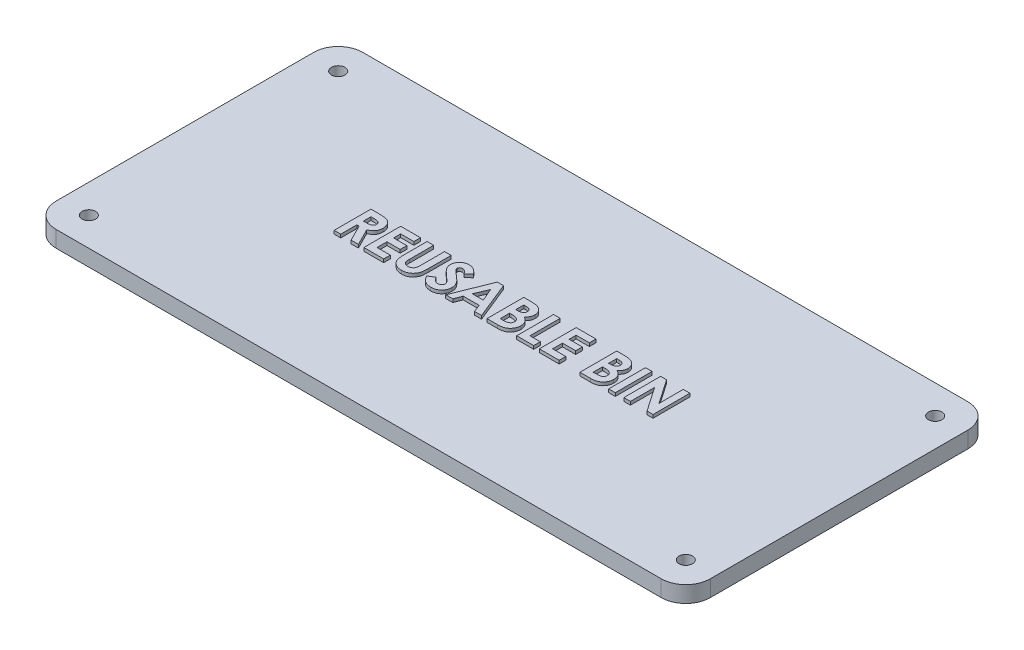
SolidWorks part; units mm, degrees
ref_plane "Front Plane" through (0, 0, 0) normal (0, 0, 1) x (1, 0, 0)
ref_plane "Top Plane" through (0, 0, 0) normal (0, 1, 0) x (1, 0, 0)
ref_plane "Right Plane" through (0, 0, 0) normal (1, 0, 0) x (0, 0, -1)
ref_plane "P1_Top_150" through (0, 150, 0) normal (0, 1, 0) x (1, 0, 0)
sketch "Sketch1" plane through (0, 150, 0) normal (0, 1, 0) x (1, 0, 0)
  line L0 (-74, -75) -> (74, -75)
  line L1 (80, -69) -> (80, -6)
  line L2 (74, 0) -> (-74, 0)
  line L3 (-80, -6) -> (-80, -69)
  arc A0 (-80, -69) -> (-74, -75) centre (-74, -69) ccw
  arc A1 (74, -75) -> (80, -69) centre (74, -69) ccw
  arc A2 (80, -6) -> (74, 0) centre (74, -6) ccw
  arc A3 (-74, 0) -> (-80, -6) centre (-74, -6) ccw
extrude "Lid" add sketch "Sketch1" along normal blind 4
sketch "Sketch2" plane through (0, 150, 0) normal (0, 1, 0) x (1, 0, 0)
  circle A0 centre (-73, -7) radius 1.65
  circle A1 centre (73, -7) radius 1.65
  circle A2 centre (-73, -68) radius 1.65
  circle A3 centre (73, -68) radius 1.65
extrude "Screw holes" cut sketch "Sketch2" along normal through all
ref_plane "P2_Top_154" through (0, 154, 0) normal (0, 1, 0) x (1, 0, 0)
sketch "Sketch3" plane through (0, 154, 0) normal (0, 1, 0) x (1, 0, 0)
  text T0 "REUSABLE BIN" font "Century Gothic" height 9
extrude "Title (raised)" add sketch "Sketch3" along normal blind 0.8
